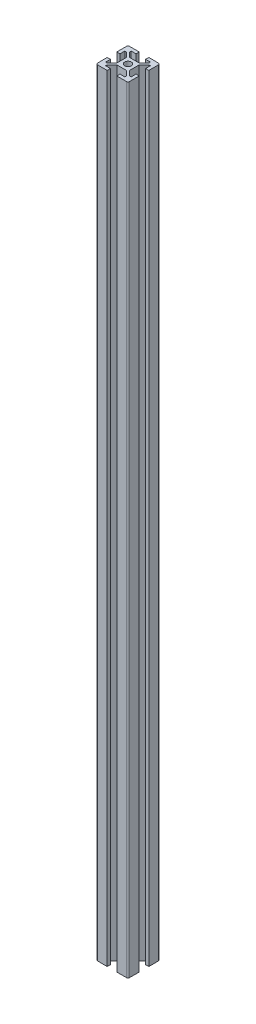
SolidWorks part; units mm, degrees
ref_plane "Front Plane" through (0, 0, 0) normal (0, 0, 1) x (1, 0, 0)
ref_plane "Top Plane" through (0, 0, 0) normal (0, 1, 0) x (1, 0, 0)
ref_plane "Right Plane" through (0, 0, 0) normal (1, 0, 0) x (0, 0, -1)
sketch "Sketch1" plane through (0, 0, 0) normal (0, 1, 0) x (1, 0, 0)
  line L5 (-3, 10) -> (-10, 10)
  line L6 (-4, 3) -> (-7, 6)
  line L7 (-4, -4) -> (4, -4)
  line L8 (-4, -4) -> (-4, 4)
  line L9 (-4, 4) -> (4, 4)
  line L10 (4, -4) -> (4, 4)
  line L11 (-8, 6) -> (-7, 6)
  line L12 (-8, 6) -> (-8, 3)
  line L16 (-3, 8) -> (-3, 10)
  line L21 (-8, 3) -> (-10, 3)
  line L22 (-6, 8) -> (-6, 7)
  line L23 (-10, 3) -> (-10, 10)
  line L24 (-3, 4) -> (-6, 7)
  line L25 (3, 10) -> (10, 10)
  line L26 (6, 8) -> (3, 8)
  line L27 (-6, 8) -> (-3, 8)
  line L28 (3, 8) -> (3, 10)
  line L29 (-10, 10) -> (-4, 4)
  line L30 (6, 8) -> (6, 7)
  line L31 (3, 4) -> (6, 7)
  line L32 (4, 3) -> (7, 6)
  line L33 (8, 6) -> (7, 6)
  line L34 (8, 6) -> (8, 3)
  line L35 (8, 3) -> (10, 3)
  line L36 (10, 3) -> (10, 10)
  line L37 (10, -3) -> (10, -10)
  line L38 (8, -6) -> (8, -3)
  line L39 (8, -3) -> (10, -3)
  line L40 (8, -6) -> (7, -6)
  line L41 (4, -3) -> (7, -6)
  line L42 (3, -4) -> (6, -7)
  line L43 (6, -8) -> (6, -7)
  line L44 (6, -8) -> (3, -8)
  line L45 (3, -8) -> (3, -10)
  line L46 (3, -10) -> (10, -10)
  line L47 (-3, -10) -> (-10, -10)
  line L48 (-6, -8) -> (-3, -8)
  line L49 (-3, -8) -> (-3, -10)
  line L50 (-6, -8) -> (-6, -7)
  line L51 (-3, -4) -> (-6, -7)
  line L52 (-4, -3) -> (-7, -6)
  line L53 (-8, -6) -> (-7, -6)
  line L54 (-8, -6) -> (-8, -3)
  line L55 (-8, -3) -> (-10, -3)
  line L56 (-10, -3) -> (-10, -10)
  circle A0 centre (0, 0) radius 2.1
  point P0 (0, 0)
  point P55 (0, 0)
  dimension "D3" = 3
  dimension "D1" = 4.2
  dimension "D2" = 4
  dimension "D4" = 4
  dimension "D5" = 6
  dimension "D7" = 8
  dimension "D8" = 10
  dimension "D6" = 4
extrude "Boss-Extrude1" add sketch "Sketch1" along normal blind 485 contours L29 L23 L21 L12 L11 L6 L8 | L5 L29 L9 L24 L22 L27 L16 | L35 L36 L25 L28 L26 L30 L31 L9 L10 L32 L33 L34 | L7 L10 L9 L8 A0 | L45 L46 L37 L39 L38 L40 L41 L10 L7 L42 L43 L44 | L55 L56 L47 L49 L48 L50 L51 L7 L8 L52 L53 L54
fillet "Fillet1" radius 1 4 edges at (-10, 242.5, 10) (-10, 242.5, -10) (10, 242.5, -10) (10, 242.5, 10)
sketch "Sketch3" plane through (0, 485, 0) normal (0, 1, 0) x (1, 0, 0)
  line L0 (-2.5757, 4) -> (-5.7, 7.1243)
  line L1 (-5.7, 7.1243) -> (-5.7, 7.7)
  line L2 (-5.7, 7.7) -> (-2.7, 7.7)
  line L3 (-2.7, 7.7) -> (-2.7, 10)
  line L4 (2.7, 10) -> (2.7, 7.7)
  line L5 (2.7, 7.7) -> (5.7, 7.7)
  line L6 (5.7, 7.7) -> (5.7, 7.1243)
  line L7 (5.7, 7.1243) -> (2.5757, 4)
  line L8 (-2.7879, 4.2121) -> (-5.7, 7.1243) construction
  line L9 (5.7, 7.1243) -> (2.7879, 4.2121) construction
  line L10 (0, 4) -> (0, 19)
  line L88 (-10, -3) -> (-10, -9)
  line L89 (-9, -10) -> (-3, -10)
  line L90 (-3, -10) -> (-3, -8)
  line L91 (-3, -8) -> (-6, -8)
  line L92 (-6, -8) -> (-6, -7)
  line L93 (-6, -7) -> (-3, -4)
  line L94 (-3, -4) -> (3, -4)
  line L95 (3, -4) -> (6, -7)
  line L96 (6, -7) -> (6, -8)
  line L97 (6, -8) -> (3, -8)
  line L98 (3, -8) -> (3, -10)
  line L99 (3, -10) -> (9, -10)
  line L100 (10, -9) -> (10, -3)
  line L101 (10, -3) -> (8, -3)
  line L102 (8, -3) -> (8, -6)
  line L103 (8, -6) -> (7, -6)
  line L104 (7, -6) -> (4, -3)
  line L105 (4, -3) -> (4, 3)
  line L106 (4, 3) -> (7, 6)
  line L107 (7, 6) -> (8, 6)
  line L108 (8, 6) -> (8, 3)
  line L109 (8, 3) -> (10, 3)
  line L110 (10, 3) -> (10, 9)
  line L111 (9, 10) -> (3, 10)
  line L112 (3, 10) -> (3, 8)
  line L113 (3, 8) -> (6, 8)
  line L114 (6, 8) -> (6, 7)
  line L115 (6, 7) -> (3, 4)
  line L116 (3, 4) -> (-3, 4)
  line L117 (-3, 4) -> (-6, 7)
  line L118 (-6, 7) -> (-6, 8)
  line L119 (-6, 8) -> (-3, 8)
  line L120 (-3, 8) -> (-3, 10)
  line L121 (-3, 10) -> (-9, 10)
  line L122 (-10, 9) -> (-10, 3)
  line L123 (-10, 3) -> (-8, 3)
  line L124 (-8, 3) -> (-8, 6)
  line L125 (-8, 6) -> (-7, 6)
  line L126 (-7, 6) -> (-4, 3)
  line L127 (-4, 3) -> (-4, -3)
  line L128 (-4, -3) -> (-7, -6)
  line L129 (-7, -6) -> (-8, -6)
  line L130 (-8, -6) -> (-8, -3)
  line L131 (-8, -3) -> (-10, -3)
  line L132 (-10, -3) -> (-10, -9)
  line L133 (-9, -10) -> (-3, -10)
  line L134 (-3, -10) -> (-3, -8)
  line L135 (-3, -8) -> (-6, -8)
  line L136 (-6, -8) -> (-6, -7)
  line L137 (-6, -7) -> (-3, -4)
  line L138 (-3, -4) -> (3, -4)
  line L139 (3, -4) -> (6, -7)
  line L140 (6, -7) -> (6, -8)
  line L141 (6, -8) -> (3, -8)
  line L142 (3, -8) -> (3, -10)
  line L143 (3, -10) -> (9, -10)
  line L144 (10, -9) -> (10, -3)
  line L145 (10, -3) -> (8, -3)
  line L146 (8, -3) -> (8, -6)
  line L147 (8, -6) -> (7, -6)
  line L148 (7, -6) -> (4, -3)
  line L149 (4, -3) -> (4, 3)
  line L150 (4, 3) -> (7, 6)
  line L151 (7, 6) -> (8, 6)
  line L152 (8, 6) -> (8, 3)
  line L153 (8, 3) -> (10, 3)
  line L154 (10, 3) -> (10, 9)
  line L155 (9, 10) -> (3, 10)
  line L156 (3, 10) -> (3, 8)
  line L157 (3, 8) -> (6, 8)
  line L158 (6, 8) -> (6, 7)
  line L159 (6, 7) -> (3, 4)
  line L160 (3, 4) -> (-3, 4)
  line L161 (-3, 4) -> (-6, 7)
  line L162 (-6, 7) -> (-6, 8)
  line L163 (-6, 8) -> (-3, 8)
  line L164 (-3, 8) -> (-3, 10)
  line L165 (-3, 10) -> (-9, 10)
  line L166 (-10, 9) -> (-10, 3)
  line L167 (-10, 3) -> (-8, 3)
  line L168 (-8, 3) -> (-8, 6)
  line L169 (-8, 6) -> (-7, 6)
  line L170 (-7, 6) -> (-4, 3)
  line L171 (-4, 3) -> (-4, -3)
  line L172 (-4, -3) -> (-7, -6)
  line L173 (-7, -6) -> (-8, -6)
  line L174 (-8, -6) -> (-8, -3)
  line L175 (-8, -3) -> (-10, -3)
  arc A8 (-10, -9) -> (-9, -10) centre (-9, -9) ccw
  arc A9 (9, -10) -> (10, -9) centre (9, -9) ccw
  arc A10 (10, 9) -> (9, 10) centre (9, 9) ccw
  arc A11 (-9, 10) -> (-10, 9) centre (-9, 9) ccw
  arc A12 (-10, -9) -> (-9, -10) centre (-9, -9) ccw
  arc A13 (9, -10) -> (10, -9) centre (9, -9) ccw
  arc A14 (10, 9) -> (9, 10) centre (9, 9) ccw
  arc A15 (-9, 10) -> (-10, 9) centre (-9, 9) ccw
  dimension "D2" = 15
  dimension "D1" = 0
  dimension "D3" = 0.3
